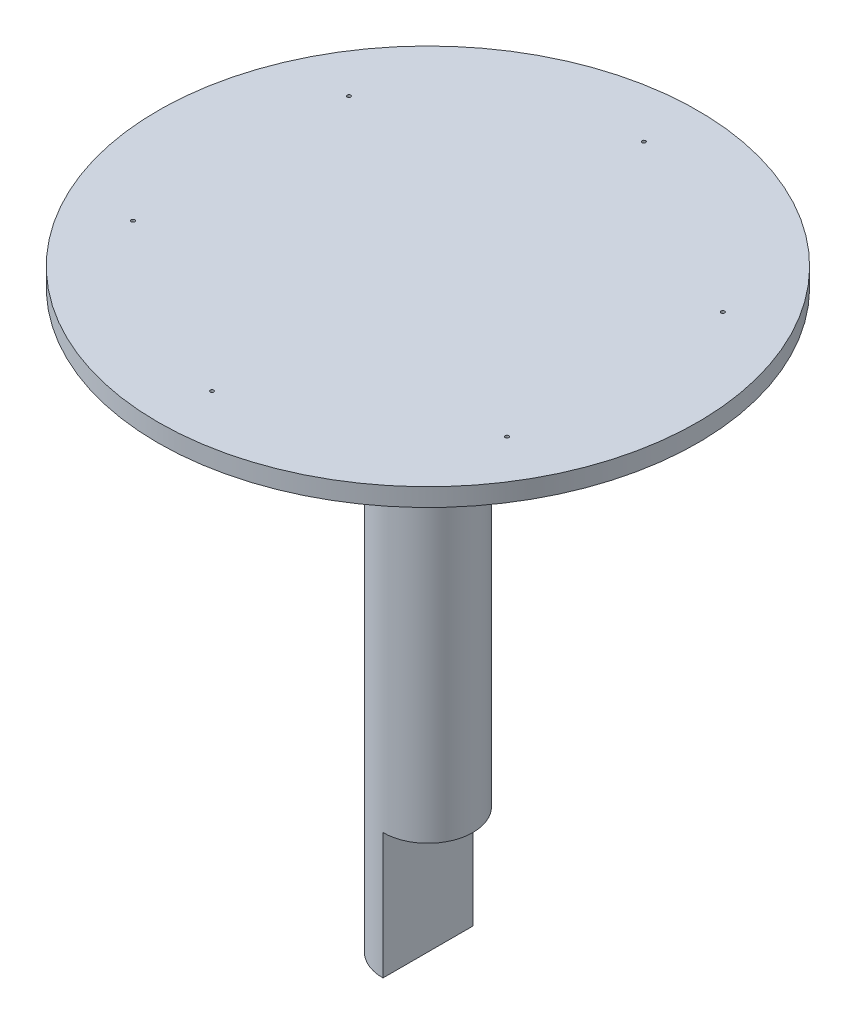
SolidWorks part; units mm, degrees
ref_plane "Plan de face" through (0, 0, 0) normal (0, 0, 1) x (1, 0, 0)
ref_plane "Plan de dessus" through (0, 0, 0) normal (0, 1, 0) x (1, 0, 0)
ref_plane "Plan de droite" through (0, 0, 0) normal (1, 0, 0) x (0, 0, -1)
sketch "Esquisse1" plane through (0, 0, 0) normal (0, 1, 0) x (1, 0, 0)
  line L0 (6.0493, -8.0024) -> (56.0493, -8.0024)
  circle A0 centre (31.0493, -8.0024) radius 25
  dimension "D1" = 50
extrude "Boss.-Extru.1" add sketch "Esquisse1" along normal blind 320 contours L0 A0 | L0 A0
sketch "Esquisse2" plane through (0, 0, 0) normal (0, -1, 0) x (-1, 0, 0)
  line L0 (-31.0493, -33.0024) -> (-31.0493, 16.9976)
  circle A0 centre (-31.0493, -8.0024) radius 25 construction
  arc A1 (-31.0493, -33.0024) -> (-31.0493, 16.9976) centre (-31.0493, -8.0024) cw
  circle M1 centre (-31.0493, -8.0024) radius 25
extrude "Enlèv. mat.-Extru.1" cut sketch "Esquisse2" against normal blind 70 contours L0 M1
sketch "Esquisse3" plane through (0, 320, 0) normal (0, 1, 0) x (1, 0, 0)
  circle A0 centre (31.0493, -8.0024) radius 150
  dimension "D2" = 300
extrude "Boss.-Extru.2" add sketch "Esquisse3" along normal blind 10
sketch "Esquisse4" plane through (0, 330, 0) normal (0, 1, 0) x (1, 0, 0)
  circle A0 centre (31.0493, -8.0024) radius 120
  circle A1 centre (31.0493, -8.0024) radius 150 construction
  circle A3 centre (-72.8738, -68.0024) radius 1
  circle A4 centre (-72.8738, 51.9976) radius 1
  circle A5 centre (31.0493, 111.9976) radius 1
  circle A6 centre (134.9723, 51.9976) radius 1
  circle A7 centre (134.9723, -68.0024) radius 1
  circle A8 centre (31.0493, -128.0024) radius 1
  dimension "D1" = 0
  dimension "D2" = 240
  dimension "D3" = 2
  dimension "D4" = 2
  dimension "D5" = 2
  dimension "D6" = 2
  dimension "D7" = 2
  dimension "D8" = 2
extrude "Enlèv. mat.-Extru.2" cut sketch "Esquisse4" against normal blind 10 contours A0 A8 | A0 A8 | A0 A3 | A0 A3 | A0 A4 | A0 A4 | A0 A5 | A0 A5 | A0 A6 | A0 A6 | A0 A7 | A0 A7
